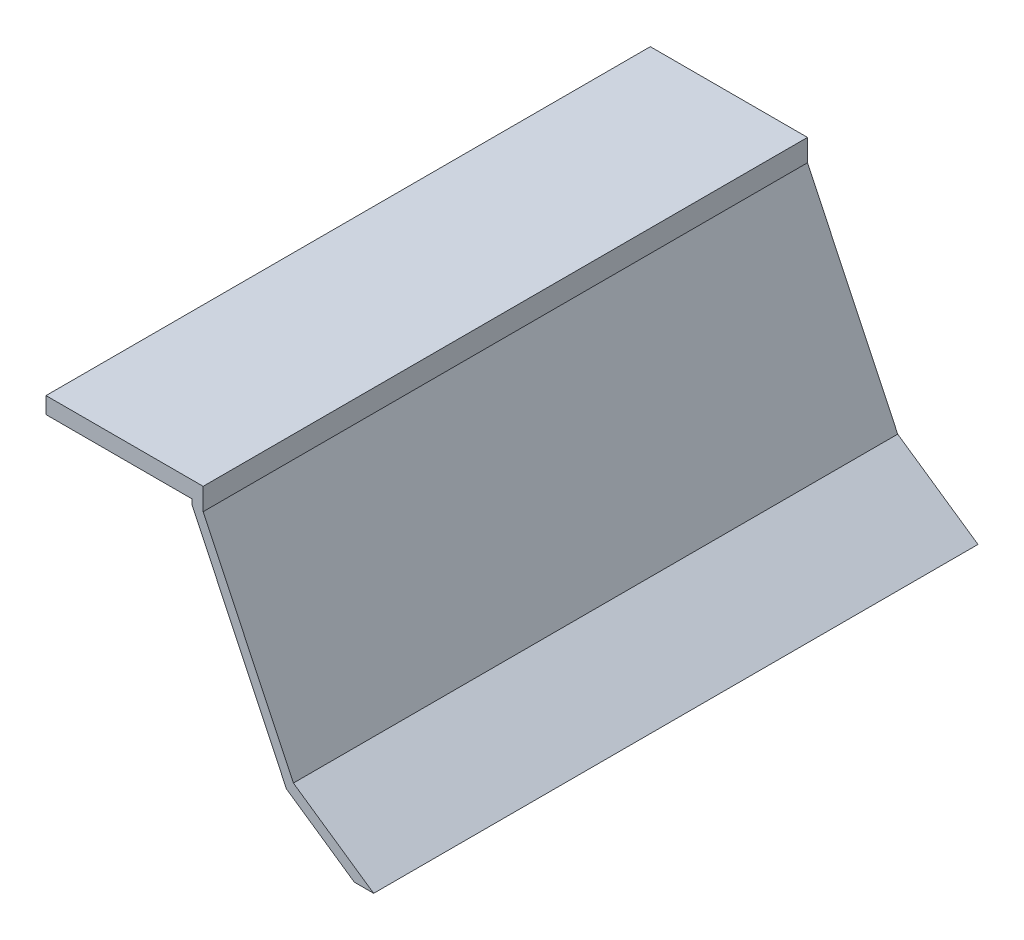
SolidWorks part; units mm, degrees
ref_plane "Front Plane" through (0, 0, 0) normal (0, 0, 1) x (1, 0, 0)
ref_plane "Top Plane" through (0, 0, 0) normal (0, 1, 0) x (1, 0, 0)
ref_plane "Right Plane" through (0, 0, 0) normal (1, 0, 0) x (0, 0, -1)
sketch "Sketch1" plane through (0, 0, 0) normal (0, 0, 1) x (1, 0, 0)
  line L0 (0, 0) -> (28.6072, 0)
  line L1 (28.6072, 0) -> (28.6072, -3.9993)
  line L2 (0, 0) -> (0, -3)
  line L3 (0, -3) -> (26.6072, -3)
  line L5 (26.6072, -4) -> (26.6072, -3)
  line L6 (28.6072, -3.9993) -> (45.0313, -38.5678)
  line L8 (43.7729, -40.1295) -> (26.6072, -4)
  line L9 (45.0313, -38.5678) -> (59.6451, -48.6443)
  line L10 (59.6451, -48.6443) -> (56.1219, -48.6443)
  line L11 (56.1219, -48.6443) -> (43.7729, -40.1295)
  dimension "D1" = 2
  dimension "D2" = 3
  dimension "D3" = 90
  dimension "D4" = 1
  dimension "D5" = 15
  dimension "D6" = 150
  dimension "D7" = 2
  dimension "D8" = 40
extrude "Boss-Extrude1" add sketch "Sketch1" along normal blind 110
